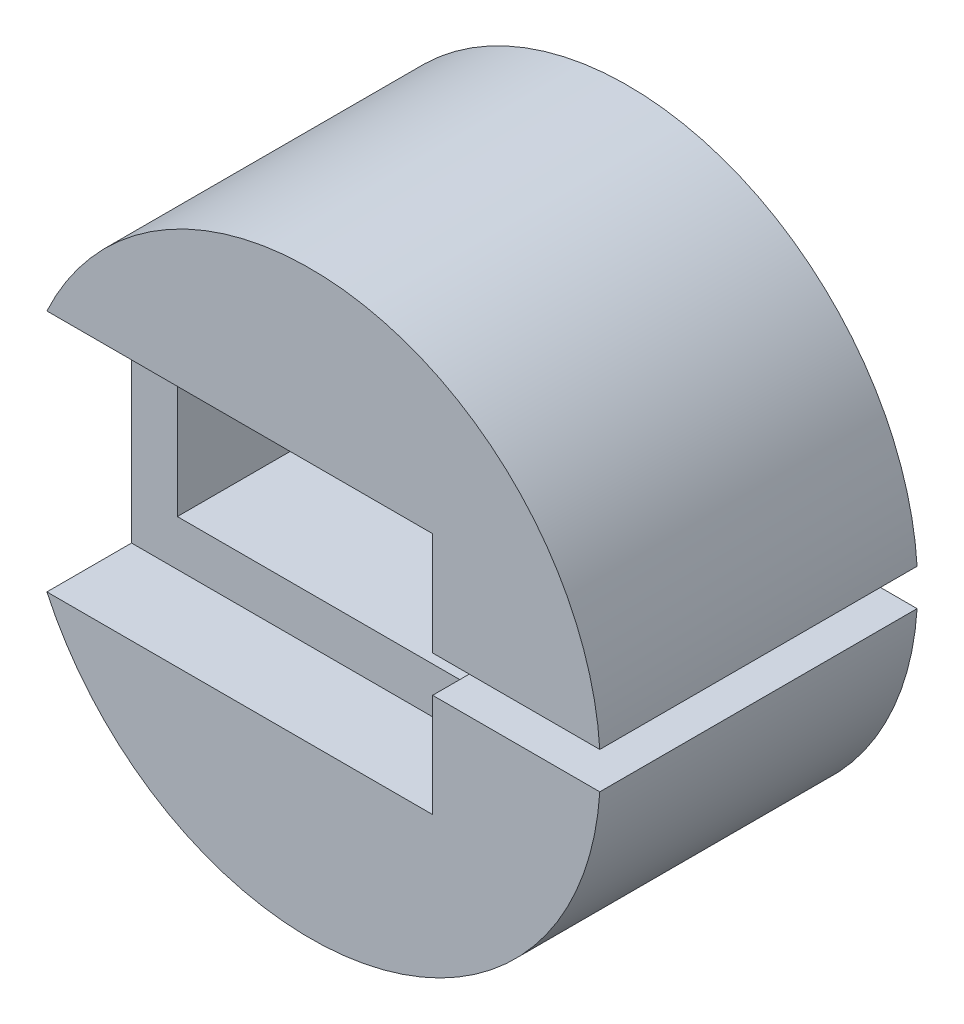
SolidWorks part; units mm, degrees
ref_plane "Front Plane" through (0, 0, 0) normal (0, 0, 1) x (1, 0, 0)
ref_plane "Top Plane" through (0, 0, 0) normal (0, 1, 0) x (1, 0, 0)
ref_plane "Right Plane" through (0, 0, 0) normal (1, 0, 0) x (0, 0, -1)
sketch "Sketch1" plane through (0, 0, 0) normal (0, 0, 1) x (1, 0, 0)
  line L10 (10.8491, 4.6) -> (12.8491, 2.6)
  line L11 (12.8491, 2.6) -> (17.3491, 2.6)
  line L12 (17.3491, 17.2491) -> (-37.3491, 17.2491)
  line L13 (-37.3491, 17.2491) -> (-37.3491, -17.2491)
  line L14 (10.8491, -10.7491) -> (10.8491, 10.7491)
  line L15 (-30.8491, -10.7491) -> (10.8491, -10.7491)
  line L16 (10.8491, 10.7491) -> (-30.8491, 10.7491)
  line L17 (-30.8491, 10.7491) -> (-30.8491, -10.7491)
  line L18 (10.8491, -10.7491) -> (10.8491, -4.6)
  line L19 (-30.8491, -10.7491) -> (10.8491, -10.7491)
  line L20 (10.8491, 10.7491) -> (-30.8491, 10.7491)
  line L21 (-30.8491, 10.7491) -> (-30.8491, -10.7491)
  line L22 (-37.3491, -17.2491) -> (17.3491, -17.2491)
  line L23 (17.3491, -17.2491) -> (17.3491, -2.6)
  line L24 (22.6, 2.1) -> (12.6, 2.1) construction
  line L29 (0, 0) -> (33.1617, 0) construction
  line L30 (12.8491, -2.6) -> (17.3491, -2.6)
  line L31 (10.8491, -4.6) -> (12.8491, -2.6)
  line L32 (10.8491, 4.6) -> (10.8491, 10.7491)
  line L33 (10.8491, -10.7491) -> (10.8491, 10.7491) construction
  line L34 (17.3491, 2.6) -> (17.3491, 17.2491)
  line L35 (17.3491, -17.2491) -> (17.3491, 17.2491) construction
  dimension "D3" = 0.5
  dimension "D4" = 135
  dimension "D5" = 2
  dimension "D1" = 0.5
  dimension "D2" = 6.5
extrude "Boss-Extrude1" add sketch "Sketch1" against normal up to surface (28 mm away)
sketch "Sketch2" plane through (0, 0, -28) normal (0, 0, -1) x (-1, 0, 0)
  line L0 (-12.8491, 2.6) -> (-41.0576, 2.6)
  line L1 (-12.8491, -2.6) -> (-41.0576, -2.6)
  line L2 (-12.8491, 2.6) -> (-12.8491, -2.6)
  line L3 (-12.8491, -2.6) -> (-17.3491, -2.6) construction
  arc A0 (-41.0576, -2.6) -> (-41.0576, 2.6) centre (0, 0) ccw
extrude "Boss-Extrude2" add sketch "Sketch2" along normal blind 5
sketch "Sketch3" plane through (0, 0, -28) normal (0, 0, 1) x (1, 0, 0)
  line L0 (41.0576, -2.6) -> (17.3491, -2.6) construction
  line L1 (17.3491, -2.6) -> (17.3491, -17.2491) construction
  line L2 (17.3491, -17.2491) -> (-37.3491, -17.2491) construction
  line L3 (-37.3491, 17.2491) -> (17.3491, 17.2491)
  line L4 (17.3491, 17.2491) -> (17.3491, 2.6)
  line L5 (17.3491, 2.6) -> (41.0576, 2.6)
  line L6 (-37.3491, 17.2491) -> (17.3491, 17.2491)
  line L7 (17.3491, 17.2491) -> (17.3491, 2.6)
  line L8 (17.3491, 2.6) -> (41.0576, 2.6)
  line L10 (41.0576, -2.6) -> (17.3491, -2.6)
  line L11 (17.3491, -2.6) -> (17.3491, -17.2491)
  line L12 (17.3491, -17.2491) -> (-37.3491, -17.2491)
  arc A0 (-37.3491, -17.2491) -> (41.0576, -2.6) centre (0, 0) ccw construction
  arc A1 (41.0576, 2.6) -> (-37.3491, 17.2491) centre (0, 0) ccw
  arc A2 (41.0576, 2.6) -> (-37.3491, 17.2491) centre (0, 0) ccw
  arc A4 (-37.3491, -17.2491) -> (41.0576, -2.6) centre (0, 0) ccw
  dimension "D1" = 0
extrude "Boss-Extrude6" add sketch "Sketch3" along normal blind 40
